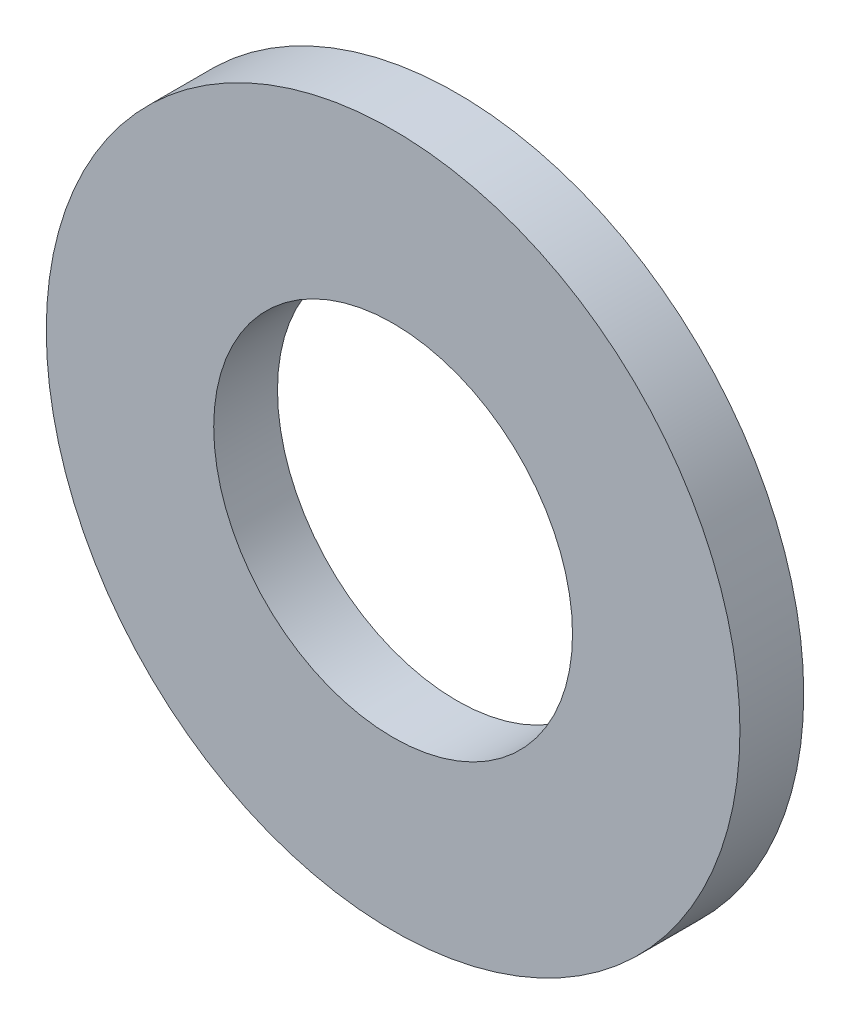
SolidWorks part; units mm, degrees
material "1.4310 (X10CrNi18-8)"
ref_plane "Front Plane" through (0, 0, 0) normal (0, 0, 1) x (1, 0, 0)
ref_plane "Top Plane" through (0, 0, 0) normal (0, 1, 0) x (1, 0, 0)
ref_plane "Right Plane" through (0, 0, 0) normal (1, 0, 0) x (0, 0, -1)
sketch "Sketch1" plane through (0, 0, 0) normal (0, 0, 1) x (1, 0, 0)
  circle A0 centre (0, 0) radius 4.35
  circle A1 centre (0, 0) radius 2.25
  dimension "OD" = 8.7
  dimension "ID1" = 4.5
extrude "Boss-Extrude1" add sketch "Sketch1" along normal blind 0.8
